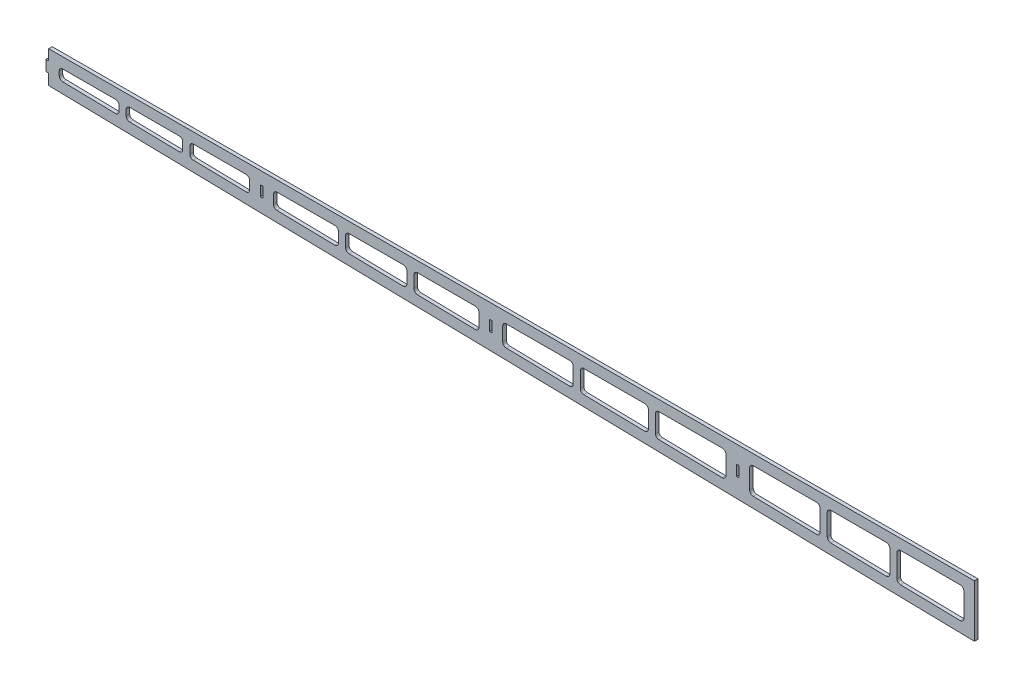
SolidWorks part; units mm, degrees
ref_plane "前视基准面" through (0, 0, 0) normal (0, 0, 1) x (1, 0, 0)
ref_plane "上视基准面" through (0, 0, 0) normal (0, 1, 0) x (1, 0, 0)
ref_plane "右视基准面" through (0, 0, 0) normal (1, 0, 0) x (0, 0, -1)
sketch "草图2" plane through (0, 0, 0) normal (0, 0, 1) x (1, 0, 0)
  line L0 (8.0538, 22.195) -> (6.5538, 22.195)
  line L1 (6.5538, 22.195) -> (6.5538, 28.195)
  line L2 (6.5538, 28.195) -> (8.0538, 28.195)
  line L3 (128.1397, 27.455) -> (129.6397, 27.455)
  line L4 (129.6397, 27.455) -> (129.6397, 21.455)
  line L5 (129.6397, 21.455) -> (128.1397, 21.455)
  line L6 (128.1397, 21.455) -> (128.1397, 27.455)
  line L7 (258.2326, 26.3184) -> (259.7326, 26.3184)
  line L8 (259.7326, 26.3184) -> (259.7326, 20.3184)
  line L9 (259.7326, 20.3184) -> (258.2326, 20.3184)
  line L10 (258.2326, 20.3184) -> (258.2326, 26.3184)
  line L11 (398.3735, 25.1616) -> (399.8735, 25.1616)
  line L12 (399.8735, 25.1616) -> (399.8735, 19.1616)
  line L13 (399.8735, 19.1616) -> (398.3735, 19.1616)
  line L14 (398.3735, 19.1616) -> (398.3735, 25.1616)
  line L15 (8.0538, 34.195) -> (8.0538, 28.195)
  line L16 (8.0538, 22.195) -> (8.0538, 16.0952)
  line L17 (8.0538, 16.0952) -> (533.4291, 5.6271)
  line L18 (533.4291, 5.6271) -> (533.4291, 35.3538)
  line L19 (533.4291, 35.3538) -> (8.0538, 34.195)
  line L20 (14.0538, 26.2126) -> (14.0538, 23.9373)
  line L21 (16.0139, 21.9377) -> (46.0139, 21.34)
  line L22 (48.0538, 23.3396) -> (48.0538, 26.2788)
  line L23 (46.0494, 28.2788) -> (16.0494, 28.2126)
  line L24 (52.0538, 26.3628) -> (52.0538, 23.1802)
  line L25 (54.0139, 21.1806) -> (82.0999, 20.621)
  line L26 (84.1397, 22.6206) -> (84.1397, 26.3628)
  line L27 (82.1397, 28.3628) -> (54.0538, 28.3628)
  line L28 (88.1397, 26.376) -> (88.1397, 22.4612)
  line L29 (90.0999, 20.4616) -> (120.0999, 19.8638)
  line L30 (122.1397, 21.8634) -> (122.1397, 26.4422)
  line L31 (120.1353, 28.4422) -> (90.1353, 28.376)
  line L32 (135.6397, 26.4808) -> (135.6397, 21.5147)
  line L33 (137.5999, 19.5151) -> (170.4999, 18.8596)
  line L34 (172.5397, 20.8592) -> (172.5397, 26.5534)
  line L35 (170.5353, 28.5534) -> (137.6353, 28.4808)
  line L36 (176.5397, 26.571) -> (176.5397, 20.6998)
  line L37 (178.4999, 18.7002) -> (209.2928, 18.0867)
  line L38 (211.3326, 20.0863) -> (211.3326, 26.6389)
  line L39 (209.3282, 28.6389) -> (178.5353, 28.571)
  line L40 (215.3326, 26.7336) -> (215.3326, 19.9269)
  line L41 (217.2928, 17.9273) -> (250.1928, 17.2717)
  line L42 (252.2326, 19.2713) -> (252.2326, 26.7336)
  line L43 (250.2326, 28.7336) -> (217.3326, 28.7336)
  line L44 (265.7326, 26.7677) -> (265.7326, 18.9226)
  line L45 (267.6928, 16.923) -> (303.6928, 16.2057)
  line L46 (305.7326, 18.2053) -> (305.7326, 26.8472)
  line L47 (303.7282, 28.8471) -> (267.7282, 28.7677)
  line L48 (309.7326, 26.8648) -> (309.7326, 18.0459)
  line L49 (311.6928, 16.0463) -> (346.3337, 15.3561)
  line L50 (348.3735, 17.3557) -> (348.3735, 26.9412)
  line L51 (346.3691, 28.9412) -> (311.7282, 28.8648)
  line L52 (352.3735, 26.9589) -> (352.3735, 17.1963)
  line L53 (354.3337, 15.1967) -> (390.3337, 14.4794)
  line L54 (392.3735, 16.479) -> (392.3735, 27.0383)
  line L55 (390.3691, 29.0383) -> (354.3691, 28.9588)
  line L56 (405.8735, 27.1607) -> (405.8735, 16.1303)
  line L57 (407.8337, 14.1307) -> (443.8337, 13.4134)
  line L58 (445.8735, 15.413) -> (445.8735, 27.1607)
  line L59 (443.8735, 29.1607) -> (407.8735, 29.1607)
  line L60 (449.8735, 27.2479) -> (449.8735, 15.2536)
  line L61 (451.8337, 13.254) -> (483.3893, 12.6253)
  line L62 (485.4291, 14.6249) -> (485.4291, 27.2479)
  line L63 (483.4291, 29.2479) -> (451.8735, 29.2479)
  line L64 (489.4291, 27.3406) -> (489.4291, 14.4655)
  line L65 (491.3893, 12.4659) -> (525.3893, 11.7884)
  line L66 (527.4291, 13.788) -> (527.4291, 27.3406)
  line L67 (525.4291, 29.3406) -> (491.4291, 29.3406)
  arc A0 (16.0494, 28.2126) -> (14.0538, 26.2126) centre (16.0538, 26.2126) ccw
  arc A1 (14.0538, 23.9373) -> (16.0139, 21.9377) centre (16.0538, 23.9373) ccw
  arc A2 (46.0139, 21.34) -> (48.0538, 23.3396) centre (46.0538, 23.3396) ccw
  arc A3 (48.0538, 26.2788) -> (46.0494, 28.2788) centre (46.0538, 26.2788) ccw
  arc A4 (54.0538, 28.3628) -> (52.0538, 26.3628) centre (54.0538, 26.3628) ccw
  arc A5 (82.0999, 20.621) -> (84.1397, 22.6206) centre (82.1397, 22.6206) ccw
  arc A6 (52.0538, 23.1802) -> (54.0139, 21.1806) centre (54.0538, 23.1802) ccw
  arc A7 (84.1397, 26.3628) -> (82.1397, 28.3628) centre (82.1397, 26.3628) ccw
  arc A8 (90.1353, 28.376) -> (88.1397, 26.376) centre (90.1397, 26.376) ccw
  arc A9 (120.0999, 19.8638) -> (122.1397, 21.8634) centre (120.1397, 21.8634) ccw
  arc A10 (88.1397, 22.4612) -> (90.0999, 20.4616) centre (90.1397, 22.4612) ccw
  arc A11 (122.1397, 26.4422) -> (120.1353, 28.4422) centre (120.1397, 26.4422) ccw
  arc A12 (137.6353, 28.4808) -> (135.6397, 26.4808) centre (137.6397, 26.4808) ccw
  arc A13 (170.4999, 18.8596) -> (172.5397, 20.8592) centre (170.5397, 20.8592) ccw
  arc A14 (135.6397, 21.5147) -> (137.5999, 19.5151) centre (137.6397, 21.5147) ccw
  arc A15 (172.5397, 26.5534) -> (170.5353, 28.5534) centre (170.5397, 26.5534) ccw
  arc A16 (178.5353, 28.571) -> (176.5397, 26.571) centre (178.5397, 26.571) ccw
  arc A17 (209.2928, 18.0867) -> (211.3326, 20.0863) centre (209.3326, 20.0863) ccw
  arc A18 (176.5397, 20.6998) -> (178.4999, 18.7002) centre (178.5397, 20.6998) ccw
  arc A19 (211.3326, 26.6389) -> (209.3282, 28.6389) centre (209.3326, 26.6389) ccw
  arc A20 (217.3326, 28.7336) -> (215.3326, 26.7336) centre (217.3326, 26.7336) ccw
  arc A21 (250.1928, 17.2717) -> (252.2326, 19.2713) centre (250.2326, 19.2713) ccw
  arc A22 (215.3326, 19.9269) -> (217.2928, 17.9273) centre (217.3326, 19.9269) ccw
  arc A23 (252.2326, 26.7336) -> (250.2326, 28.7336) centre (250.2326, 26.7336) ccw
  arc A24 (267.7282, 28.7677) -> (265.7326, 26.7677) centre (267.7326, 26.7677) ccw
  arc A25 (303.6928, 16.2057) -> (305.7326, 18.2053) centre (303.7326, 18.2053) ccw
  arc A26 (265.7326, 18.9226) -> (267.6928, 16.923) centre (267.7326, 18.9226) ccw
  arc A27 (305.7326, 26.8472) -> (303.7282, 28.8471) centre (303.7326, 26.8472) ccw
  arc A28 (311.7282, 28.8648) -> (309.7326, 26.8648) centre (311.7326, 26.8648) ccw
  arc A29 (346.3337, 15.3561) -> (348.3735, 17.3557) centre (346.3735, 17.3557) ccw
  arc A30 (309.7326, 18.0459) -> (311.6928, 16.0463) centre (311.7326, 18.0459) ccw
  arc A31 (348.3735, 26.9412) -> (346.3691, 28.9412) centre (346.3735, 26.9412) ccw
  arc A32 (354.3691, 28.9588) -> (352.3735, 26.9589) centre (354.3735, 26.9589) ccw
  arc A33 (390.3337, 14.4794) -> (392.3735, 16.479) centre (390.3735, 16.479) ccw
  arc A34 (352.3735, 17.1963) -> (354.3337, 15.1967) centre (354.3735, 17.1963) ccw
  arc A35 (392.3735, 27.0383) -> (390.3691, 29.0383) centre (390.3735, 27.0383) ccw
  arc A36 (407.8735, 29.1607) -> (405.8735, 27.1607) centre (407.8735, 27.1607) ccw
  arc A37 (443.8337, 13.4134) -> (445.8735, 15.413) centre (443.8735, 15.413) ccw
  arc A38 (405.8735, 16.1303) -> (407.8337, 14.1307) centre (407.8735, 16.1303) ccw
  arc A39 (445.8735, 27.1607) -> (443.8735, 29.1607) centre (443.8735, 27.1607) ccw
  arc A40 (451.8735, 29.2479) -> (449.8735, 27.2479) centre (451.8735, 27.2479) ccw
  arc A41 (483.3893, 12.6253) -> (485.4291, 14.6249) centre (483.4291, 14.6249) ccw
  arc A42 (449.8735, 15.2536) -> (451.8337, 13.254) centre (451.8735, 15.2536) ccw
  arc A43 (485.4291, 27.2479) -> (483.4291, 29.2479) centre (483.4291, 27.2479) ccw
  arc A44 (491.4291, 29.3406) -> (489.4291, 27.3406) centre (491.4291, 27.3406) ccw
  arc A45 (525.3893, 11.7884) -> (527.4291, 13.788) centre (525.4291, 13.788) ccw
  arc A46 (489.4291, 14.4655) -> (491.3893, 12.4659) centre (491.4291, 14.4655) ccw
  arc A47 (527.4291, 27.3406) -> (525.4291, 29.3406) centre (525.4291, 27.3406) ccw
extrude "凸台-拉伸2" add sketch "草图2" along normal blind 2
